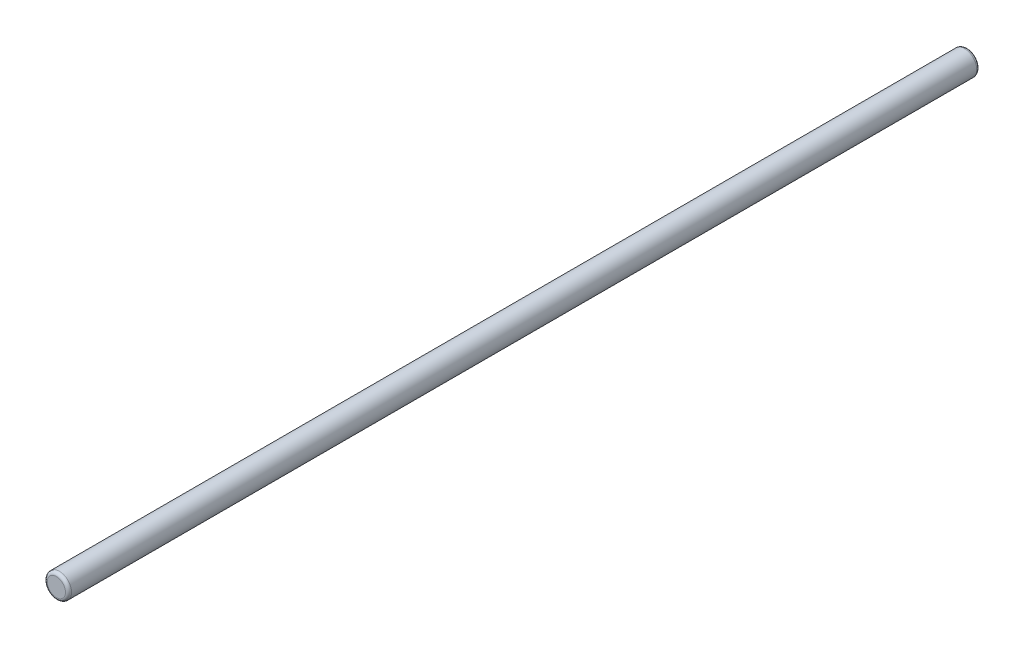
SolidWorks part; units mm, degrees
ref_plane "Front Plane" through (0, 0, 0) normal (0, 0, 1) x (1, 0, 0)
ref_plane "Top Plane" through (0, 0, 0) normal (0, 1, 0) x (1, 0, 0)
ref_plane "Right Plane" through (0, 0, 0) normal (1, 0, 0) x (0, 0, -1)
sketch "Sketch1" plane through (0, 0, 0) normal (0, 0, 1) x (1, 0, 0)
  circle A0 centre (0, 0) radius 4
  dimension "D1" = 8
extrude "Boss-Extrude1" add sketch "Sketch1" along normal blind 300
fillet "Fillet1" radius 1 2 edges at (4, 0, 0) (4, 0, 300)
